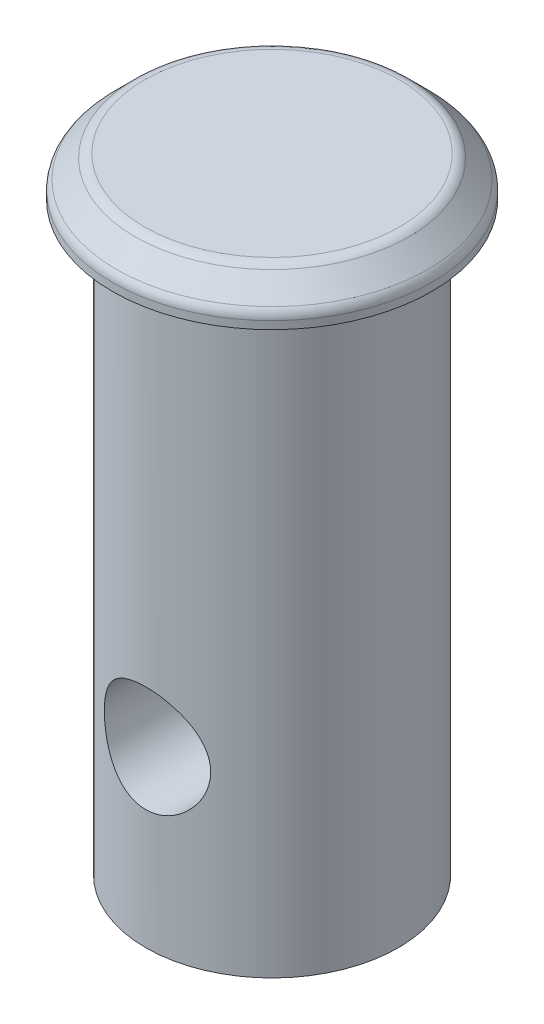
SolidWorks part; units mm, degrees
ref_plane "Front Plane" through (0, 0, 0) normal (0, 0, 1) x (1, 0, 0)
ref_plane "Top Plane" through (0, 0, 0) normal (0, 1, 0) x (1, 0, 0)
ref_plane "Right Plane" through (0, 0, 0) normal (1, 0, 0) x (0, 0, -1)
sketch "Sketch1" plane through (0, 0, 0) normal (0, 1, 0) x (1, 0, 0)
  circle A0 centre (0, 0) radius 4.75
  dimension "D1" = 9.5
extrude "Boss-Extrude1" add sketch "Sketch1" along normal blind 22
sketch "Sketch2" plane through (0, 22, 0) normal (0, 1, 0) x (1, 0, 0)
  circle A0 centre (0, 0) radius 6
  dimension "D1" = 12
extrude "Boss-Extrude2" add sketch "Sketch2" along normal blind 1.5
chamfer "Chamfer1" distance 1 angle 45 1 edges at (0, 23.5, 6)
fillet "Fillet1" radius 0.5 2 edges at (0, 22.5, 6) (0, 23.5, 5)
sketch "Sketch3" plane through (0, 0, 0) normal (0, 0, 1) x (1, 0, 0)
  line L0 (-4.75, 0) -> (4.75, 0) construction
  circle A0 centre (0, 6.5) radius 2
  dimension "D2" = 4
  dimension "D1" = 6.5
extrude "Cut-Extrude1" cut sketch "Sketch3" against normal through all both and the other way through all
